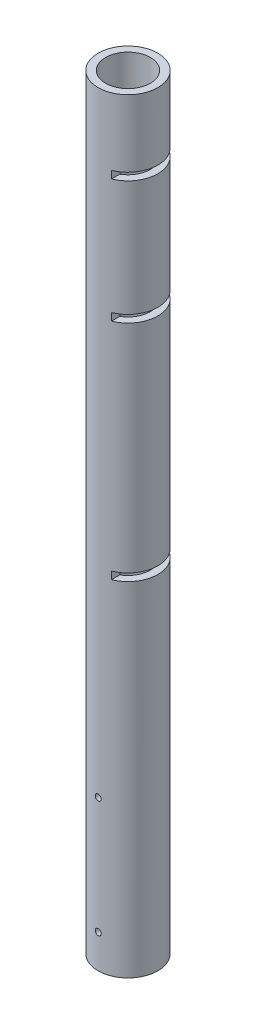
SolidWorks part; units mm, degrees
ref_plane "Front Plane" through (0, 0, 0) normal (0, 0, 1) x (1, 0, 0)
ref_plane "Top Plane" through (0, 0, 0) normal (0, 1, 0) x (1, 0, 0)
ref_plane "Right Plane" through (0, 0, 0) normal (1, 0, 0) x (0, 0, -1)
sketch "Sketch1" plane through (0, 0, 0) normal (0, 1, 0) x (1, 0, 0)
  circle A0 centre (0, 0) radius 25.4
  circle A1 centre (0, 0) radius 19.05
  dimension "D1" = 6.35
  dimension "D2" = 50.8
extrude "Boss-Extrude1" add sketch "Sketch1" along normal blind 650.875
sketch "Sketch2" plane through (0, 0, 0) normal (0, 0, 1) x (1, 0, 0)
  line L0 (0, 0) -> (0, 28.575) construction
  line L1 (-25.4, 0) -> (25.4, 0) construction
  line L2 (0, 28.575) -> (0, 127.7937) construction
  line L3 (25.4, 650.875) -> (25.4, 593.725) construction
  line L4 (25.4, 0) -> (25.4, 650.875) construction
  line L5 (25.4, 593.725) -> (9.525, 593.725)
  line L6 (9.525, 593.725) -> (9.525, 587.375)
  line L7 (9.525, 587.375) -> (25.4, 587.375)
  line L8 (25.4, 587.375) -> (25.4, 593.725)
  line L9 (25.4, 587.375) -> (25.4, 488.95) construction
  line L10 (25.4, 488.95) -> (9.525, 488.95)
  line L11 (9.525, 488.95) -> (9.525, 482.6)
  line L12 (9.525, 482.6) -> (25.4, 482.6)
  line L13 (25.4, 482.6) -> (25.4, 488.95)
  line L14 (9.525, 590.55) -> (25.4, 590.55) construction
  line L15 (9.525, 485.775) -> (25.4, 485.775) construction
  line L16 (25.4, 650.875) -> (-25.4, 650.875) construction
  line L17 (25.4, 298.45) -> (9.525, 298.45)
  line L18 (9.525, 298.45) -> (9.525, 292.1)
  line L19 (9.525, 292.1) -> (25.4, 292.1)
  line L20 (25.4, 292.1) -> (25.4, 298.45)
  line L21 (9.525, 295.275) -> (25.4, 295.275) construction
  circle A0 centre (0, 28.575) radius 2.54
  circle A1 centre (0, 127.7937) radius 2.54
  dimension "D1" = 5.08
  dimension "D2" = 28.575
  dimension "D3" = 127.7937
  dimension "D4" = 15.875
  dimension "D5" = 6.35
  dimension "D6" = 60.325
  dimension "D7" = 165.1
  dimension "D8" = 355.6
extrude "Cut-Extrude1" cut sketch "Sketch2" against normal through all both and the other way through all
